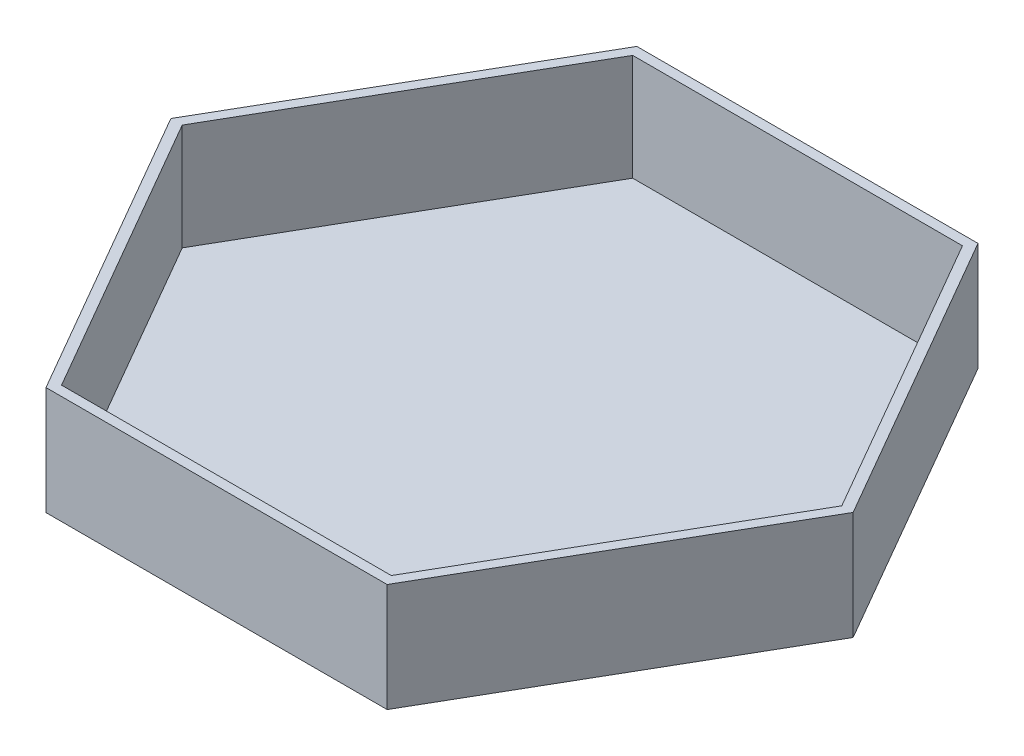
SolidWorks part; units mm, degrees
ref_plane "Front Plane" through (0, 0, 0) normal (0, 0, 1) x (1, 0, 0)
ref_plane "Top Plane" through (0, 0, 0) normal (0, 1, 0) x (1, 0, 0)
ref_plane "Right Plane" through (0, 0, 0) normal (1, 0, 0) x (0, 0, -1)
sketch "Sketch1" plane through (0, 0, 0) normal (0, 1, 0) x (1, 0, 0)
  line L1 (173.2051, 0) -> (86.6025, 150)
  line L2 (86.6025, 150) -> (-86.6025, 150)
  line L3 (-86.6025, 150) -> (-173.2051, 0)
  line L4 (-173.2051, 0) -> (-86.6025, -150)
  line L5 (-86.6025, -150) -> (86.6025, -150)
  line L6 (86.6025, -150) -> (173.2051, 0)
  circle A0 centre (0, 0) radius 150 construction
  dimension "D1" = 300
extrude "Boss-Extrude1" add sketch "Sketch1" along normal blind 55
shell "Shell1" thickness 5
